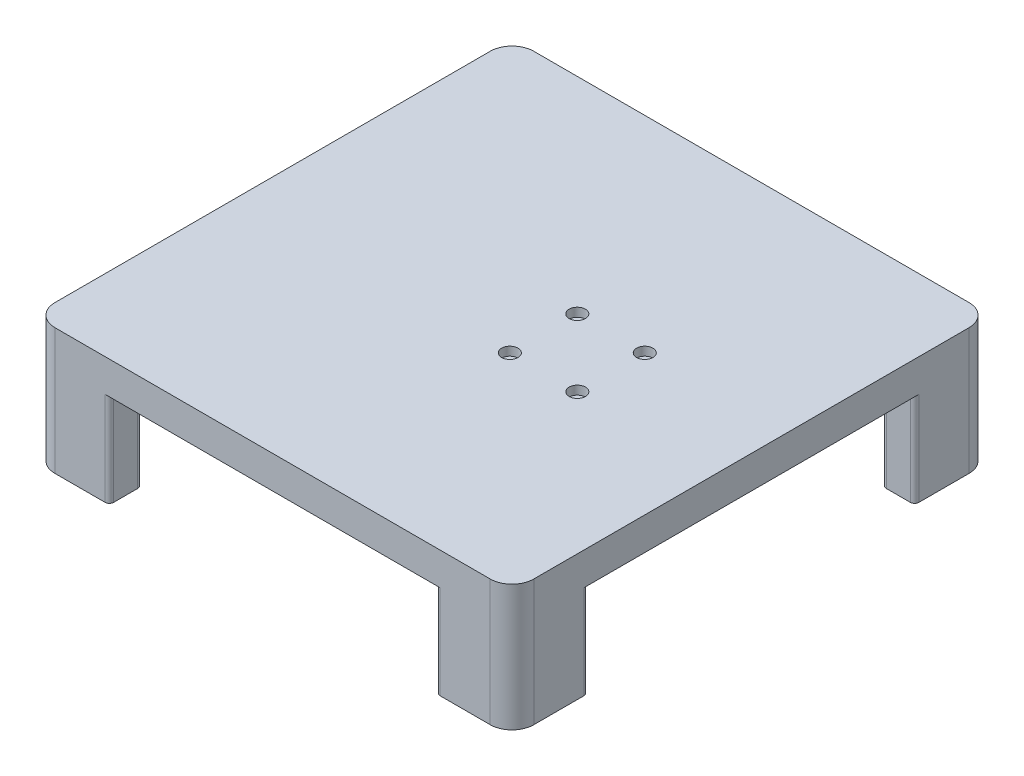
SolidWorks part; units mm, degrees
ref_plane "Front Plane" through (0, 0, 0) normal (0, 0, 1) x (1, 0, 0)
ref_plane "Top Plane" through (0, 0, 0) normal (0, 1, 0) x (1, 0, 0)
ref_plane "Right Plane" through (0, 0, 0) normal (1, 0, 0) x (0, 0, -1)
sketch "Sketch1" plane through (0, 0, 0) normal (0, 1, 0) x (1, 0, 0)
  line L0 (45.4253, -33.3559) -> (45.4253, 33.3559) construction
  line L1 (-110, -110) -> (110, -110)
  line L2 (-110, -110) -> (-110, 110)
  line L3 (-110, 110) -> (110, 110)
  line L4 (110, -110) -> (110, 110)
  line L5 (0, 110) -> (0, -110) construction
  line L6 (-110, 0) -> (110, 0) construction
  line L7 (30, -19.5827) -> (30, 19.5827) construction
  circle A0 centre (45.5, 15.5) radius 1.75
  circle A1 centre (45.5, -15.5) radius 1.75
  circle A2 centre (14.5, -15.5) radius 1.75
  circle A8 centre (14.5, 15.5) radius 1.75
  point P0 (0, 0)
  point P14 (45.4253, 0)
  point P19 (30, 0)
  dimension "D3" = 31
  dimension "D4" = 15.5
  dimension "D5" = 3.5
  dimension "D7" = 30
  dimension "D1" = 220
  dimension "D2" = 220
  dimension "D6" = 45.4253
extrude "Boss-Extrude1" add sketch "Sketch1" along normal blind 15
fillet "Fillet1" radius 10 4 edges at (-110, 7.5, 110) (-110, 7.5, -110) (110, 7.5, -110) (110, 7.5, 110)
sketch "Sketch2" plane through (0, 0, 0) normal (0, -1, 0) x (1, 0, 0)
  line L0 (-75, 95) -> (-85, 95)
  line L1 (-95, 85) -> (-95, 75)
  line L4 (100, 110) -> (-100, 110)
  line L5 (-110, 100) -> (-110, -100)
  line L6 (-100, -110) -> (100, -110)
  line L7 (110, -100) -> (110, 100)
  line L8 (-75, 110) -> (-100, 110)
  line L9 (-110, 100) -> (-110, 75)
  line L12 (-95, 75) -> (-110, 75)
  line L13 (-75, 95) -> (-75, 110)
  line L14 (100, 110) -> (-100, 110) construction
  line L15 (92.2403, 95) -> (-95, 95) construction
  line L16 (-95, 95) -> (-95, -95) construction
  line L17 (-110, 100) -> (-110, -100) construction
  line L18 (-95, -95) -> (94.9278, -95) construction
  line L19 (94.9278, -95) -> (92.2403, 95) construction
  line L20 (110, -100) -> (107.0711, 107.0711) construction
  line L21 (-100, -110) -> (100, -110) construction
  line L22 (55, 0) -> (-55, 0) construction
  line L23 (-75, -95) -> (-75, -110)
  line L24 (-75, -95) -> (-85, -95)
  line L25 (-95, -85) -> (-95, -75)
  line L26 (-95, -75) -> (-110, -75)
  line L27 (-110, -100) -> (-110, -75)
  line L28 (-75, -110) -> (-100, -110)
  line L29 (0, -55) -> (0, 55) construction
  line L30 (75, -95) -> (85, -95)
  line L31 (95, -85) -> (95, -75)
  line L32 (95, -75) -> (110, -75)
  line L33 (110, -100) -> (110, -75)
  line L34 (75, -110) -> (100, -110)
  line L35 (75, -95) -> (75, -110)
  line L36 (75, 95) -> (75, 110)
  line L37 (75, 95) -> (85, 95)
  line L38 (95, 85) -> (95, 75)
  line L39 (95, 75) -> (110, 75)
  line L40 (110, 100) -> (110, 75)
  line L41 (75, 110) -> (100, 110)
  arc A4 (-100, 110) -> (-110, 100) centre (-100, 100) ccw
  arc A5 (-110, -100) -> (-100, -110) centre (-100, -100) ccw
  arc A6 (100, -110) -> (110, -100) centre (100, -100) ccw
  arc A7 (110, 100) -> (100, 110) centre (100, 100) ccw
  arc A8 (-100, 110) -> (-110, 100) centre (-100, 100) ccw
  arc A12 (92.2403, 95) -> (92.2403, 95) centre (92.2403, 95) ccw construction
  arc A13 (94.9278, -95) -> (94.9278, -95) centre (94.9278, -95) ccw construction
  arc A14 (-95, -95) -> (-95, -95) centre (-95, -95) ccw construction
  arc A15 (107.0711, 107.0711) -> (100, 110) centre (100, 100) ccw construction
  arc A16 (-95, -85) -> (-85, -95) centre (-85, -85) ccw
  arc A17 (100, -110) -> (110, -100) centre (100, -100) ccw construction
  arc A18 (-110, -100) -> (-100, -110) centre (-100, -100) ccw construction
  arc A19 (-95, 85) -> (-85, 95) centre (-85, 85) cw
  arc A20 (-95, 95) -> (-95, 95) centre (-95, 95) ccw construction
  arc A21 (-100, -110) -> (-110, -100) centre (-100, -100) cw
  arc A22 (95, -85) -> (85, -95) centre (85, -85) cw
  arc A23 (100, -110) -> (110, -100) centre (100, -100) ccw
  arc A24 (95, 85) -> (85, 95) centre (85, 85) ccw
  arc A25 (100, 110) -> (110, 100) centre (100, 100) cw
  dimension "D5" = 10
  dimension "D3" = 35
  dimension "D4" = 35
  dimension "D1" = 0
  dimension "D2" = 15
extrude "Boss-Extrude2" add sketch "Sketch2" along normal blind 43
sketch "Sketch3" plane through (0, -43, 0) normal (0, -1, 0) x (1, 0, 0)
  line L0 (0, 0) -> (33.5462, 0) construction
  line L1 (-75, 110) -> (75, 110) construction
  line L2 (-110, -75) -> (-110, -100) construction
  arc A0 (-103, -85) -> (-85, -103) centre (-85, -85) ccw construction
  arc A1 (-106.325, -85) -> (-85, -106.325) centre (-85, -85) ccw
  arc A2 (-99.675, -85) -> (-85, -99.675) centre (-85, -85) ccw
  arc A3 (-99.675, -85) -> (-106.325, -85) centre (-103, -85) ccw
  arc A4 (-85, -106.325) -> (-85, -99.675) centre (-85, -103) ccw
  circle A5 centre (0, 0) radius 10 construction
  arc A6 (-85, 103) -> (-103, 85) centre (-85, 85) ccw construction
  arc A7 (-85, 106.325) -> (-106.325, 85) centre (-85, 85) ccw
  arc A8 (-85, 99.675) -> (-99.675, 85) centre (-85, 85) ccw
  arc A9 (-85, 99.675) -> (-85, 106.325) centre (-85, 103) ccw
  arc A10 (-106.325, 85) -> (-99.675, 85) centre (-103, 85) ccw
  arc A11 (103, 85) -> (85, 103) centre (85, 85) ccw construction
  arc A12 (106.325, 85) -> (85, 106.325) centre (85, 85) ccw
  arc A13 (99.675, 85) -> (85, 99.675) centre (85, 85) ccw
  arc A14 (99.675, 85) -> (106.325, 85) centre (103, 85) ccw
  arc A15 (85, 106.325) -> (85, 99.675) centre (85, 103) ccw
  arc A16 (85, -103) -> (103, -85) centre (85, -85) ccw construction
  arc A17 (85, -106.325) -> (106.325, -85) centre (85, -85) ccw
  arc A18 (85, -99.675) -> (99.675, -85) centre (85, -85) ccw
  arc A19 (85, -99.675) -> (85, -106.325) centre (85, -103) ccw
  arc A20 (106.325, -85) -> (99.675, -85) centre (103, -85) ccw
  point P0 (0, 0)
  point P5 (-97.7279, -97.7279)
  point P21 (-97.7279, 97.7279)
  point P29 (97.7279, 97.7279)
  point P38 (97.7279, -97.7279)
  point P44 (0, 0)
  dimension "D3" = 18
  dimension "D4" = 85
  dimension "D7" = 20
  dimension "D8" = 25
  dimension "D9" = 4
  dimension "D1" = 6.65
  dimension "D2" = 90
  dimension "D5" = 85
  dimension "D6" = 110
extrude "Cut-Extrude1" cut sketch "Sketch3" against normal blind 31
fillet "Fillet2" radius 2 16 edges at (110, -21.5, -75) (95, -21.5, -75) (75, -21.5, -95) (75, -21.5, -110) (-75, -21.5, -95) (-75, -21.5, -110) (-95, -21.5, -75) (-110, -21.5, -75) (-110, -21.5, 75) (-75, -21.5, 110) (-75, -21.5, 95) (-95, -21.5, 75) (75, -21.5, 110) (75, -21.5, 95) (110, -21.5, 75) (95, -21.5, 75)
sketch "Sketch5" plane through (0, 15, 0) normal (0, 1, 0) x (1, 0, 0)
  line L16 (-110, 100) -> (-110, -100)
  line L17 (-100, -110) -> (100, -110)
  line L18 (110, -100) -> (110, 100)
  line L19 (100, 110) -> (-100, 110)
  line L20 (-110, 100) -> (-110, -100)
  line L21 (-100, -110) -> (100, -110)
  line L22 (110, -100) -> (110, 100)
  line L23 (100, 110) -> (-100, 110)
  circle A6 centre (14.5, 15.5) radius 3.75
  circle A7 centre (14.5, 15.5) radius 3.75
  arc A16 (-110, -100) -> (-100, -110) centre (-100, -100) ccw
  arc A17 (100, -110) -> (110, -100) centre (100, -100) ccw
  arc A18 (110, 100) -> (100, 110) centre (100, 100) ccw
  arc A19 (-100, 110) -> (-110, 100) centre (-100, 100) ccw
  arc A20 (-110, -100) -> (-100, -110) centre (-100, -100) ccw
  arc A21 (100, -110) -> (110, -100) centre (100, -100) ccw
  arc A22 (110, 100) -> (100, 110) centre (100, 100) ccw
  arc A23 (-100, 110) -> (-110, 100) centre (-100, 100) ccw
  circle A30 centre (45.5, 15.5) radius 3.75
  circle A31 centre (45.5, 15.5) radius 3.75
  circle A33 centre (14.5, -15.5) radius 3.75
  circle A34 centre (14.5, -15.5) radius 3.75
  circle A36 centre (45.5, -15.5) radius 3.75
  circle A37 centre (45.5, -15.5) radius 3.75
  dimension "D2" = 0
  dimension "D3" = 2
  dimension "D4" = 2
  dimension "22" = 2
  dimension "D6" = 2
extrude "Cut-Extrude2" cut sketch "Sketch5" against normal blind 4 contours A7 | A31 | A37 | A34
